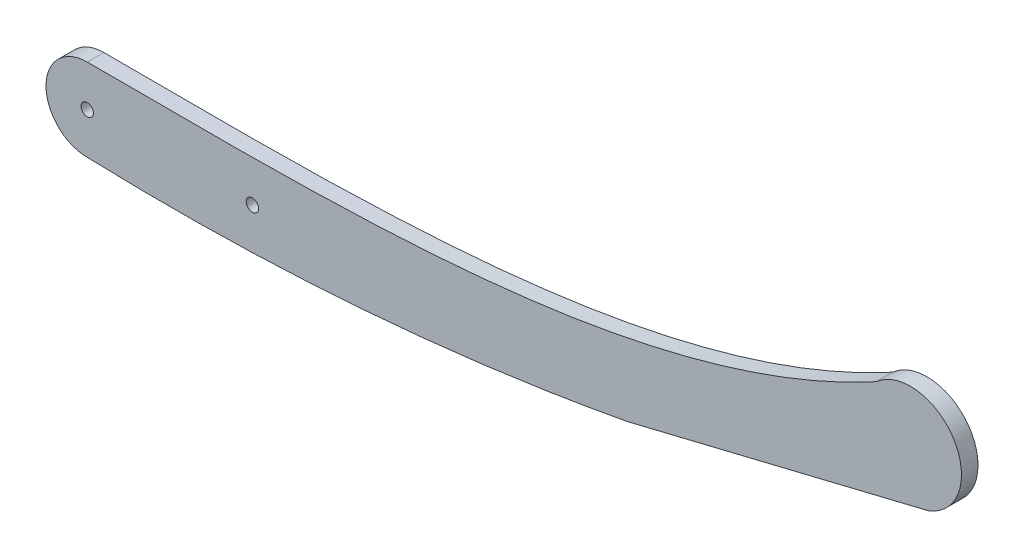
SolidWorks part; units mm, degrees
ref_plane "前视基准面" through (0, 0, 0) normal (0, 0, 1) x (1, 0, 0)
ref_plane "上视基准面" through (0, 0, 0) normal (0, 1, 0) x (1, 0, 0)
ref_plane "右视基准面" through (0, 0, 0) normal (1, 0, 0) x (0, 0, -1)
sketch "草图1" plane through (0, 0, 0) normal (0, 0, 1) x (1, 0, 0)
  line L0 (0, 0) -> (160, 0) construction
  line L1 (0, 0) -> (-40, 0) construction
  line L4 (80, 0) -> (80, -30.7931) construction
  circle A0 centre (0, 0) radius 1.5
  arc A1 (0, 10) -> (-0.1831, 9.9983) centre (0, 0) ccw
  arc A2 (163.684, 17.7234) -> (151.1303, 38.5197) centre (159.3882, 29.3174) ccw
  arc A3 (0, -10) -> (0.6746, -9.9772) centre (0, 0) ccw
  circle A4 centre (-40, 0) radius 1.5
  arc A5 (-39.9623, 9.9999) -> (-40, -10) centre (-40, 0) ccw
  arc A6 (155.7258, 41.1268) -> (151.1303, 38.5197) centre (159.3882, 29.3174) ccw
  spline S0 degree 3 poles (-40, 10) (22.9073, 9.8816) (95.2353, 7.9762) (151.1303, 38.5197) knots 0 0 0 0 0.832549 0.832549 0.832549 0.832549
  spline S1 degree 3 poles (-40, -10) (4.0259, -11.4538) (47.6497, -8.1205) (90.8713, 0) knots 0 0 0 0 0.65351 0.65351 0.65351 0.65351
  spline S2 degree 1 poles (90.8713, 0) (163.684, 17.7234) knots 0 0 1 1
  dimension "D2" = 40
  dimension "D1" = 200
extrude "凸台-拉伸1" add sketch "草图1" along normal blind 4 contours S1 S2 A2 S0 A5 A0 A4
